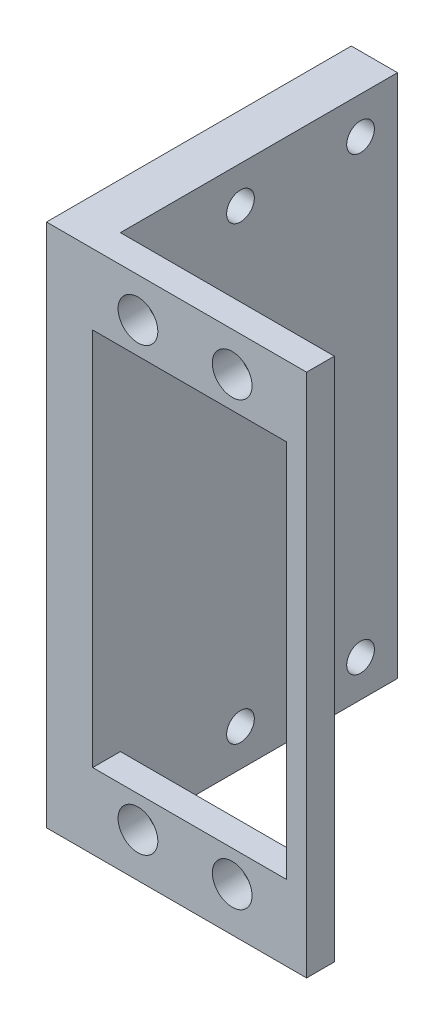
SolidWorks part; units mm, degrees
ref_plane "Front Plane" through (0, 0, 0) normal (0, 0, 1) x (1, 0, 0)
ref_plane "Top Plane" through (0, 0, 0) normal (0, 1, 0) x (1, 0, 0)
ref_plane "Right Plane" through (0, 0, 0) normal (1, 0, 0) x (0, 0, -1)
sketch "Sketch1" plane through (0, 0, 0) normal (0, 0, 1) x (1, 0, 0)
  line L9 (11.7044, 17.6097) -> (11.7044, -39.1936)
  line L10 (-11.4535, 17.6097) -> (11.7044, 17.6097)
  line L11 (-11.4535, -39.1936) -> (11.7044, -39.1936)
  line L13 (-11.4535, -39.1936) -> (-11.4535, 17.6097)
  point P0 (0, 0)
extrude "Boss-Extrude1" add sketch "Sketch1" along normal blind 3
sketch "Sketch2" plane through (0, 0, 3) normal (0, 0, 1) x (1, 0, 0)
  line L1 (9.5288, -31.0417) -> (-12.0367, -31.0417)
  line L2 (9.5288, -31.0417) -> (9.5288, 9.9868)
  line L3 (9.5288, 9.9868) -> (-12.0367, 9.9868)
  line L4 (-12.0367, -31.0417) -> (-12.0367, 9.9868)
  line L5 (9.5288, -31.0417) -> (-12.0367, 9.9868) construction
  line L6 (9.5288, 9.9868) -> (-12.0367, -31.0417) construction
  point P0 (-1.254, -10.5274)
  dimension "D1" = 21.5654
  dimension "D2" = 41.0285
extrude "Cut-Extrude1" cut sketch "Sketch2" against normal blind 3
sketch "Sketch3" plane through (0, 0, 0) normal (0, 0, -1) x (-1, 0, 0)
  line L32 (-11.7044, 17.6097) -> (11.4535, 17.6097) construction
  line L33 (11.4535, -39.1936) -> (16.4535, -39.1936)
  line L34 (11.4535, -39.1936) -> (11.4535, 17.6097)
  line L35 (11.4535, 17.6097) -> (16.4535, 17.6097)
  line L36 (16.4535, -39.1936) -> (16.4535, 17.6097)
  dimension "D1" = 5
extrude "Boss-Extrude2" add sketch "Sketch3" along normal blind 30 and the other way blind 3
sketch "Sketch4" plane through (0, 0, 0) normal (0, 0, -1) x (-1, 0, 0)
  line L0 (-11.7044, 17.6097) -> (11.4535, 17.6097) construction
  line L2 (-11.7044, -39.1936) -> (-11.7044, 17.6097) construction
  line L3 (-9.5288, -31.0417) -> (11.4535, -31.0417) construction
  circle A0 centre (-3.6465, 13.3726) radius 2.15
  circle A1 centre (6.5535, 13.3726) radius 2.15
  circle A2 centre (-3.6465, -34.4274) radius 2.15
  circle A3 centre (6.5535, -34.4274) radius 2.15
  dimension "D1" = 4.3
  dimension "D2" = 4.3
  dimension "D3" = 4.3
  dimension "D4" = 4.3
  dimension "D7" = 10.2
  dimension "D5" = 4.2371
  dimension "D6" = 8.0579
  dimension "D8" = 3.3858
  dimension "D9" = 8.0579
  dimension "D10" = 10.2
extrude "Cut-Extrude2" cut sketch "Sketch4" against normal blind 10
sketch "Sketch5" plane through (-11.4535, 0, 0) normal (1, 0, 0) x (0, 0, -1)
  line L0 (0, 17.6097) -> (30, 17.6097) construction
  line L1 (30, 17.6097) -> (30, -39.1936) construction
  line L2 (26, 13.6097) -> (13, 13.6097) construction
  line L3 (26, 13.6097) -> (26, 12.1097) construction
  line L4 (30, -10.792) -> (3.5324, -10.792) construction
  circle A0 centre (26, 13.6097) radius 1.5
  circle A1 centre (13, 13.6097) radius 1.5
  circle A3 centre (26, -35.1936) radius 1.5
  circle A4 centre (13, -35.1936) radius 1.5
  dimension "D1" = 3
  dimension "D4" = 3
  dimension "D5" = 13
  dimension "D2" = 4
  dimension "D3" = 4
extrude "Cut-Extrude3" cut sketch "Sketch5" against normal blind 10
